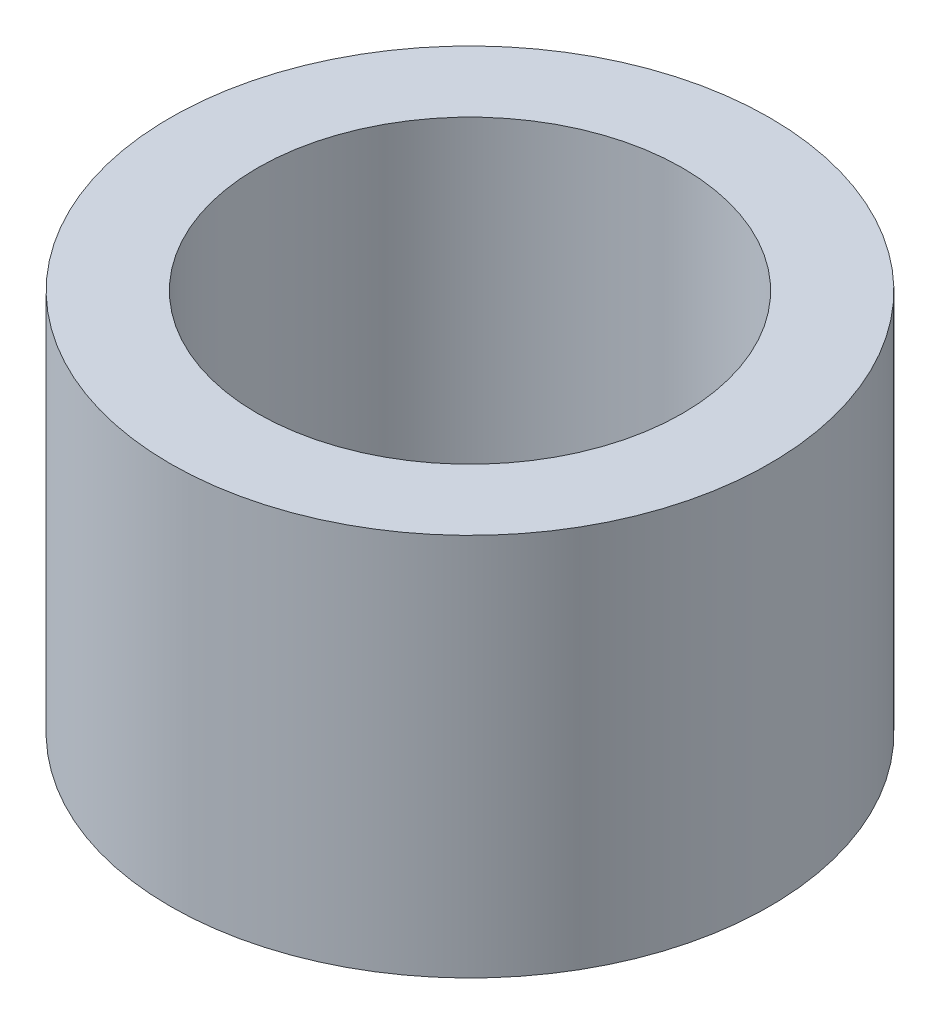
SolidWorks part; units mm, degrees
ref_plane "Front Plane" through (0, 0, 0) normal (0, 0, 1) x (1, 0, 0)
ref_plane "Top Plane" through (0, 0, 0) normal (0, 1, 0) x (1, 0, 0)
ref_plane "Right Plane" through (0, 0, 0) normal (1, 0, 0) x (0, 0, -1)
sketch "Sketch2" plane through (0, 0, 0) normal (0, 1, 0) x (1, 0, 0)
  circle A0 centre (0, 0) radius 6.1
  circle A1 centre (0, 0) radius 8.6
  dimension "D1" = 12.2
  dimension "D2" = 2.5
extrude "Boss-Extrude1" add sketch "Sketch2" along normal blind 11
